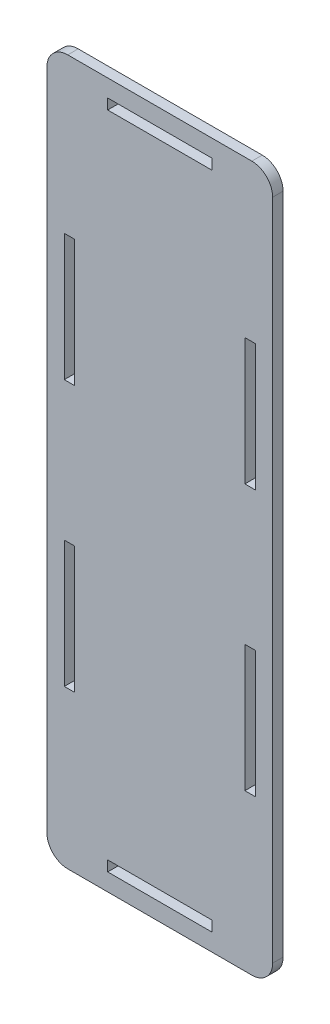
SolidWorks part; units mm, degrees
ref_plane "Front Plane" through (0, 0, 0) normal (0, 0, 1) x (1, 0, 0)
ref_plane "Top Plane" through (0, 0, 0) normal (0, 1, 0) x (1, 0, 0)
ref_plane "Right Plane" through (0, 0, 0) normal (1, 0, 0) x (0, 0, -1)
sketch "Sketch1" plane through (0, 0, 0) normal (0, 0, 1) x (1, 0, 0)
  line L1 (-26.5, 101.5) -> (26.5, 101.5)
  line L2 (-32.5, 95.5) -> (-32.5, -95.5)
  line L3 (-26.5, -101.5) -> (26.5, -101.5)
  line L4 (32.5, 95.5) -> (32.5, -95.5)
  line L5 (-32.5, 101.5) -> (32.5, -101.5) construction
  line L6 (-32.5, -101.5) -> (32.5, 101.5) construction
  arc A0 (26.5, 101.5) -> (32.5, 95.5) centre (26.5, 95.5) cw
  arc A1 (26.5, -101.5) -> (32.5, -95.5) centre (26.5, -95.5) ccw
  arc A2 (-26.5, -101.5) -> (-32.5, -95.5) centre (-26.5, -95.5) cw
  arc A3 (-32.5, 95.5) -> (-26.5, 101.5) centre (-26.5, 95.5) cw
  point P0 (0, 0)
  dimension "D3" = 6
  dimension "D1" = 65
  dimension "D2" = 203
extrude "Boss-Extrude1" add sketch "Sketch1" along normal blind 3
sketch "Sketch2" plane through (0, 0, 3) normal (0, 0, 1) x (1, 0, 0)
  line L0 (0, 96.5) -> (0, -96.5) construction
  line L1 (-27.5, 96.5) -> (27.5, 96.5)
  line L2 (-27.5, 96.5) -> (-27.5, -96.5)
  line L3 (-27.5, -96.5) -> (27.5, -96.5)
  line L4 (27.5, 96.5) -> (27.5, -96.5)
  line L5 (-27.5, 96.5) -> (27.5, -96.5) construction
  line L6 (-27.5, -96.5) -> (27.5, 96.5) construction
  line L7 (-27.5, 0) -> (27.5, 0) construction
  line L8 (24.5, -20) -> (27.5, -20)
  line L9 (-15, 96.5) -> (15, 96.5)
  line L10 (-15, 96.5) -> (-15, 93.5)
  line L11 (-15, 93.5) -> (15, 93.5)
  line L12 (15, 96.5) -> (15, 93.5)
  line L13 (-15, 96.5) -> (15, 93.5) construction
  line L14 (-15, 93.5) -> (15, 96.5) construction
  line L15 (24.5, 56.5) -> (27.5, 56.5)
  line L16 (24.5, 56.5) -> (24.5, 20)
  line L17 (24.5, 20) -> (27.5, 20)
  line L18 (27.5, 56.5) -> (27.5, 20)
  line L19 (24.5, 56.5) -> (27.5, 20) construction
  line L20 (24.5, 20) -> (27.5, 56.5) construction
  line L21 (27.5, -56.5) -> (27.5, -20)
  line L22 (24.5, -56.5) -> (27.5, -56.5)
  line L23 (24.5, -56.5) -> (24.5, -20)
  line L24 (-15, -93.5) -> (15, -93.5)
  line L25 (15, -96.5) -> (15, -93.5)
  line L26 (-15, -96.5) -> (15, -96.5)
  line L27 (-15, -96.5) -> (-15, -93.5)
  line L28 (-24.5, 20) -> (-27.5, 20)
  line L29 (-27.5, 56.5) -> (-27.5, 20)
  line L30 (-24.5, 56.5) -> (-27.5, 56.5)
  line L31 (-24.5, 56.5) -> (-24.5, 20)
  line L32 (-24.5, -56.5) -> (-24.5, -20)
  line L33 (-24.5, -56.5) -> (-27.5, -56.5)
  line L34 (-27.5, -56.5) -> (-27.5, -20)
  line L35 (-24.5, -20) -> (-27.5, -20)
  point P0 (0, 0)
  point P10 (0, 95)
  point P15 (26, 38.25)
  dimension "D1" = 55
  dimension "D2" = 193
  dimension "D3" = 30
  dimension "D4" = 3
  dimension "D5" = 1.5
  dimension "D6" = 58.25
  dimension "D7" = 36.5
  dimension "D8" = 3
extrude "Cut-Extrude1" cut sketch "Sketch2" against normal blind 3 contours L31 L28 L29 L30 | L11 L12 L9 L10 | L16 L17 L18 L15 | L23 L8 L21 L22 | L24 L25 L26 L27 | L32 L35 L34 L33
